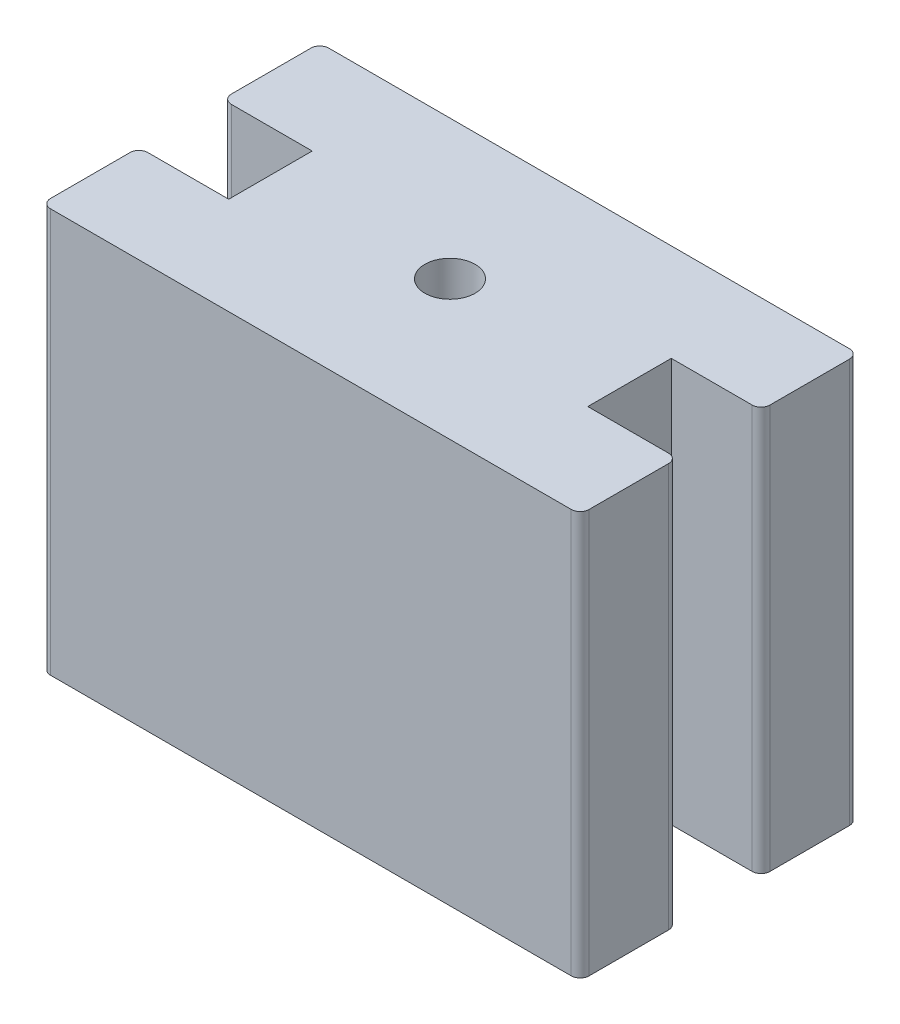
SolidWorks part; units mm, degrees
ref_plane "Front Plane" through (0, 0, 0) normal (0, 0, 1) x (1, 0, 0)
ref_plane "Top Plane" through (0, 0, 0) normal (0, 1, 0) x (1, 0, 0)
ref_plane "Right Plane" through (0, 0, 0) normal (1, 0, 0) x (0, 0, -1)
sketch "Sketch1" plane through (0, 0, 0) normal (0, 1, 0) x (1, 0, 0)
  line L0 (20, 4.65) -> (29, 4.65)
  line L1 (-20, 15.5) -> (20, 15.5)
  line L2 (-20, 4.65) -> (-20, -4.65)
  line L3 (-20, -15.5) -> (20, -15.5)
  line L4 (20, 4.65) -> (20, -4.65)
  line L7 (-29, 15.5) -> (29, 15.5)
  line L8 (-30, 14.5) -> (-30, 5.65)
  line L9 (-29, 4.65) -> (-20, 4.65)
  line L10 (30, 14.5) -> (30, 5.65)
  line L11 (-29, -15.5) -> (29, -15.5)
  line L12 (-30, -14.5) -> (-30, -5.65)
  line L13 (-29, -4.65) -> (-20, -4.65)
  line L14 (30, -14.5) -> (30, -5.65)
  line L15 (20, -4.65) -> (29, -4.65)
  arc A0 (-29, -15.5) -> (-30, -14.5) centre (-29, -14.5) cw
  arc A1 (-30, -5.65) -> (-29, -4.65) centre (-29, -5.65) cw
  arc A2 (-30, 5.65) -> (-29, 4.65) centre (-29, 5.65) ccw
  arc A3 (-29, 15.5) -> (-30, 14.5) centre (-29, 14.5) ccw
  arc A4 (29, -15.5) -> (30, -14.5) centre (29, -14.5) ccw
  arc A5 (29, -4.65) -> (30, -5.65) centre (29, -5.65) cw
  arc A6 (29, 4.65) -> (30, 5.65) centre (29, 5.65) ccw
  arc A7 (29, 15.5) -> (30, 14.5) centre (29, 14.5) cw
  circle A8 centre (0, 0) radius 2.8
  point P0 (0, 0)
  dimension "D6" = 1
  dimension "D7" = 1
  dimension "D8" = 5.6
  dimension "D1" = 40
  dimension "D2" = 31
  dimension "D3" = 9.3
  dimension "D4" = 10
  dimension "D5" = 10
extrude "Boss-Extrude1" add sketch "Sketch1" along normal blind 45 contours A7 L7 L1 A3 L8 A2 L9 L2 L13 A1 L12 A0 L11 L3 A4 L14 A5 L15 L4 L0 A6 L10 A8
